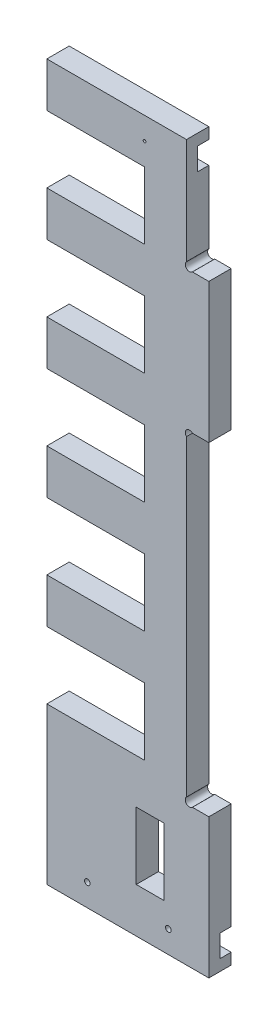
SolidWorks part; units mm, degrees
ref_plane "Plan de face" through (0, 0, 0) normal (0, 0, 1) x (1, 0, 0)
ref_plane "Plan de dessus" through (0, 0, 0) normal (0, 1, 0) x (1, 0, 0)
ref_plane "Plan de droite" through (0, 0, 0) normal (1, 0, 0) x (0, 0, -1)
sketch "Esquisse1" plane through (0, 0, 0) normal (0, 0, 1) x (1, 0, 0)
  line L0 (-47.2113, 8.0146) -> (30.577, 8.0146) construction
  line L1 (30.577, 186.1359) -> (30.577, 224.0146)
  line L2 (-19.423, 144.0146) -> (-19.423, 128.0146)
  line L3 (-19.423, -31.9854) -> (30.577, -31.9854)
  line L4 (30.577, 131.8932) -> (30.577, 20.1359)
  line L5 (-47.2113, 48.0146) -> (30.577, 48.0146) construction
  line L6 (-47.2113, 88.0146) -> (30.577, 88.0146) construction
  line L7 (-47.2113, 128.0146) -> (30.577, 128.0146) construction
  line L8 (-47.2113, 168.0146) -> (30.577, 168.0146) construction
  line L9 (22.577, 168.0146) -> (22.577, -39.7784) construction
  line L10 (-25.8665, 24.0146) -> (35.1678, 24.0146) construction
  line L11 (-22.7631, 64.0146) -> (35.1678, 64.0146) construction
  line L12 (-22.7631, 104.0146) -> (35.1678, 104.0146) construction
  line L13 (-22.7631, 144.0146) -> (35.1678, 144.0146) construction
  line L14 (5.577, 173.4418) -> (5.577, -34.7699) construction
  line L15 (15.577, 173.4418) -> (15.577, -34.7699) construction
  line L16 (-19.423, 144.0146) -> (15.577, 144.0146)
  line L17 (-19.423, 128.0146) -> (15.577, 128.0146)
  line L18 (-19.423, 64.0146) -> (-19.423, 48.0146)
  line L19 (-19.423, 104.0146) -> (15.577, 104.0146)
  line L20 (15.577, 128.0146) -> (15.577, 104.0146)
  line L21 (-19.423, 88.0146) -> (15.577, 88.0146)
  line L22 (-19.423, 24.0146) -> (-19.423, -31.9854)
  line L23 (-19.423, 64.0146) -> (15.577, 64.0146)
  line L24 (15.577, 88.0146) -> (15.577, 64.0146)
  line L25 (-19.423, 48.0146) -> (15.577, 48.0146)
  line L26 (30.577, 224.0146) -> (-19.423, 224.0146)
  line L27 (-19.423, 24.0146) -> (15.577, 24.0146)
  line L28 (15.577, 48.0146) -> (15.577, 24.0146)
  line L29 (12.577, 8.0146) -> (22.577, 8.0146)
  line L30 (12.577, 8.0146) -> (12.577, -15.9854)
  line L31 (12.577, -15.9854) -> (22.577, -15.9854)
  line L32 (22.577, 8.0146) -> (22.577, -15.9854)
  line L33 (15.577, 144.0146) -> (15.577, 168.0146)
  line L34 (-19.423, 104.0146) -> (-19.423, 88.0146)
  line L35 (-19.423, 168.0146) -> (15.577, 168.0146)
  line L36 (-19.423, 168.0146) -> (-19.423, 184.0146)
  line L37 (-19.423, 184.0146) -> (15.577, 184.0146)
  line L38 (-21.6389, -27.9854) -> (30.577, -27.9854) construction
  line L39 (-19.423, 224.0146) -> (-19.423, 208.0146)
  line L40 (-19.423, 208.0146) -> (15.577, 208.0146)
  line L41 (15.577, 208.0146) -> (15.577, 184.0146)
  line L42 (30.577, -31.9854) -> (38.577, -31.9854)
  line L43 (38.577, -31.9854) -> (38.577, 18.0146)
  line L44 (38.577, 18.0146) -> (32.6983, 18.0146)
  line L45 (32.6983, 184.0146) -> (38.577, 184.0146)
  line L46 (38.577, 184.0146) -> (38.577, 134.0146)
  line L47 (38.577, 134.0146) -> (32.6983, 134.0146)
  arc A0 (30.577, 20.1359) -> (32.6983, 18.0146) centre (31.6377, 19.0752) ccw
  arc A1 (30.577, 186.1359) -> (32.6983, 184.0146) centre (31.6377, 185.0752) ccw
  arc A2 (32.6983, 134.0146) -> (30.577, 131.8932) centre (31.6377, 132.9539) ccw
  dimension "D15" = 4
  dimension "D1" = 40
  dimension "D2" = 40
  dimension "D3" = 40
  dimension "D4" = 40
  dimension "D5" = 40
  dimension "D6" = 8
  dimension "D7" = 16
  dimension "D8" = 16
  dimension "D9" = 16
  dimension "D10" = 16
  dimension "D11" = 50
  dimension "D12" = 10
  dimension "D13" = 16
  dimension "D14" = 166
extrude "Boss.-Extru.1" add sketch "Esquisse1" along normal blind 8
sketch "Esquisse2" plane through (0, 0, 0) normal (0, 0, -1) x (-1, 0, 0)
  line L0 (19.423, 184.0146) -> (19.423, 168.0146) construction
  line L1 (19.423, 172.0146) -> (-28.5105, 172.0146)
  line L2 (19.423, 172.0146) -> (19.423, 180.0146)
  line L3 (19.423, 180.0146) -> (-28.5105, 180.0146)
  line L4 (-30.577, 174.1359) -> (-30.577, 177.8932)
  line L5 (-15.577, 184.0146) -> (19.423, 184.0146) construction
  line L6 (19.423, 168.0146) -> (-15.577, 168.0146) construction
  line L7 (19.423, 144.0146) -> (19.423, 128.0146) construction
  line L8 (19.423, 140.0146) -> (-18.4557, 140.0146)
  line L9 (19.423, 140.0146) -> (19.423, 132.0146)
  line L10 (19.423, 132.0146) -> (-18.4557, 132.0146)
  line L11 (-20.577, 137.8932) -> (-20.577, 134.1359)
  line L12 (19.423, 104.0146) -> (19.423, 88.0146) construction
  line L13 (19.423, 100.0146) -> (-18.4557, 100.0146)
  line L14 (19.423, 100.0146) -> (19.423, 92.0146)
  line L15 (19.423, 92.0146) -> (-18.4557, 92.0146)
  line L16 (-20.577, 97.8932) -> (-20.577, 94.1359)
  line L17 (19.423, 64.0146) -> (19.423, 48.0146) construction
  line L18 (19.423, 60.0146) -> (-18.4557, 60.0146)
  line L19 (19.423, 60.0146) -> (19.423, 52.0146)
  line L20 (19.423, 52.0146) -> (-18.4557, 52.0146)
  line L21 (-20.577, 57.8932) -> (-20.577, 54.1359)
  line L22 (19.423, 24.0146) -> (19.423, -31.9854) construction
  line L23 (19.423, 20.0146) -> (-18.4557, 20.0146)
  line L24 (19.423, 20.0146) -> (19.423, 12.0146)
  line L25 (19.423, 12.0146) -> (-18.4557, 12.0146)
  line L26 (-20.577, 17.8932) -> (-20.577, 14.1359)
  line L27 (-15.577, 144.0146) -> (19.423, 144.0146) construction
  line L28 (19.423, 128.0146) -> (-15.577, 128.0146) construction
  line L29 (-15.577, 104.0146) -> (19.423, 104.0146) construction
  line L30 (19.423, 88.0146) -> (-15.577, 88.0146) construction
  line L31 (-15.577, 64.0146) -> (19.423, 64.0146) construction
  line L32 (19.423, 48.0146) -> (-15.577, 48.0146) construction
  line L33 (-15.577, 24.0146) -> (19.423, 24.0146) construction
  line L34 (19.423, 224.0146) -> (19.423, 208.0146) construction
  line L35 (19.423, 220.0146) -> (-31.9447, 220.0146)
  line L36 (19.423, 220.0146) -> (19.423, 212.0146)
  line L37 (19.423, 212.0146) -> (-31.9447, 212.0146)
  line L38 (-31.9447, 220.0146) -> (-31.9447, 212.0146)
  line L39 (-30.577, 224.0146) -> (19.423, 224.0146) construction
  line L40 (19.423, 208.0146) -> (-15.577, 208.0146) construction
  line L41 (-38.577, -27.9854) -> (19.423, -27.9854)
  line L42 (-38.577, -31.9854) -> (-38.577, 18.0146) construction
  line L43 (-38.577, -20.0538) -> (19.423, -20.0538)
  line L44 (-30.577, 186.1359) -> (-30.577, 224.0146) construction
  line L45 (19.423, -27.9854) -> (19.423, -20.0538)
  line L46 (19.423, -31.9854) -> (-38.577, -31.9854) construction
  line L47 (-38.577, -20.0538) -> (-38.577, -27.9854)
  arc A0 (-28.5105, 180.0146) -> (-30.577, 177.8932) centre (-29.3721, 178.7867) ccw
  arc A1 (-30.577, 174.1359) -> (-28.5105, 172.0146) centre (-29.3721, 173.2424) ccw
  arc A2 (-20.577, 134.1359) -> (-18.4557, 132.0146) centre (-19.5163, 133.0752) ccw
  arc A3 (-18.4557, 140.0146) -> (-20.577, 137.8932) centre (-19.5163, 138.9539) ccw
  arc A4 (-20.577, 94.1359) -> (-18.4557, 92.0146) centre (-19.5163, 93.0752) ccw
  arc A5 (-18.4557, 100.0146) -> (-20.577, 97.8932) centre (-19.5163, 98.9539) ccw
  arc A6 (-20.577, 54.1359) -> (-18.4557, 52.0146) centre (-19.5163, 53.0752) ccw
  arc A7 (-18.4557, 60.0146) -> (-20.577, 57.8932) centre (-19.5163, 58.9539) ccw
  arc A8 (-20.577, 14.1359) -> (-18.4557, 12.0146) centre (-19.5163, 13.0752) ccw
  arc A9 (-18.4557, 20.0146) -> (-20.577, 17.8932) centre (-19.5163, 18.9539) ccw
  dimension "D11" = 4
  dimension "D15" = 1.5
  dimension "D16" = 1.5
  dimension "D1" = 4
  dimension "D2" = 4
  dimension "D3" = 4
  dimension "D4" = 4
  dimension "D5" = 4
  dimension "D6" = 4
  dimension "D7" = 4
  dimension "D8" = 4
  dimension "D9" = 4
  dimension "D10" = 8
  dimension "D12" = 4
  dimension "D13" = 4
  dimension "D14" = 0
extrude "Enlèv. mat.-Extru.1" cut sketch "Esquisse2" against normal blind 4
sketch "Esquisse3" plane through (0, 0, 4) normal (0, 0, -1) x (-1, 0, 0)
  line L0 (-30.577, 216.0146) -> (-15.577, 216.0146) construction
  line L1 (-30.577, 212.0146) -> (-30.577, 220.0146) construction
  line L2 (19.423, -24.0196) -> (-38.577, -24.0196) construction
  line L5 (19.423, -27.9854) -> (19.423, -20.0538) construction
  line L6 (-38.577, -20.0538) -> (-38.577, -27.9854) construction
  line L7 (-9.577, -24.0196) -> (-9.577, -20.0538) construction
  line L8 (19.423, -20.0538) -> (-38.577, -20.0538) construction
  line L9 (-9.577, -20.0538) -> (19.423, -20.0538) construction
  line L10 (19.423, -20.0538) -> (19.423, -24.0196) construction
  line L11 (4.923, -20.0538) -> (4.923, -24.0196) construction
  circle A0 centre (-15.577, 216.0146) radius 0.5
  circle A1 centre (4.923, -24.0196) radius 1
  circle A2 centre (-24.077, -24.0196) radius 1
extrude "Enlèv. mat.-Extru.2" cut sketch "Esquisse3" against normal blind 4
